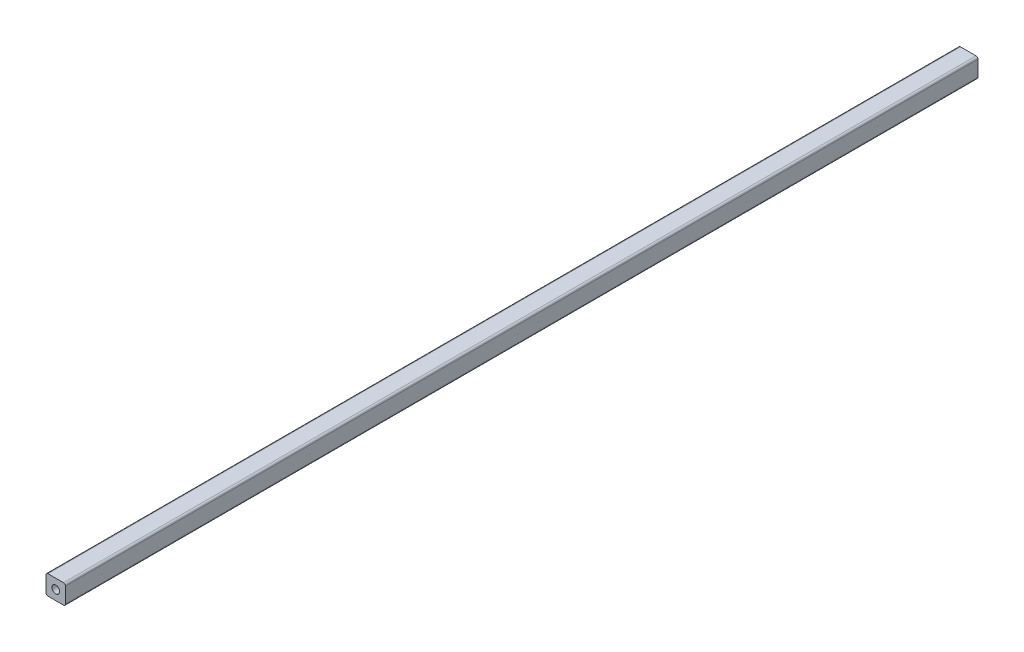
SolidWorks part; units mm, degrees
ref_plane "Front Plane" through (0, 0, 0) normal (0, 0, 1) x (1, 0, 0)
ref_plane "Top Plane" through (0, 0, 0) normal (0, 1, 0) x (1, 0, 0)
ref_plane "Right Plane" through (0, 0, 0) normal (1, 0, 0) x (0, 0, -1)
sketch "Sketch1" plane through (0, 0, 0) normal (0, 0, 1) x (1, 0, 0)
  line L1 (-25.4, 25.4) -> (25.4, 25.4)
  line L2 (-25.4, 25.4) -> (-25.4, -25.4)
  line L3 (-25.4, -25.4) -> (25.4, -25.4)
  line L4 (25.4, 25.4) -> (25.4, -25.4)
  line L5 (-25.4, 25.4) -> (25.4, -25.4) construction
  line L6 (-25.4, -25.4) -> (25.4, 25.4) construction
  circle A0 centre (0, 0) radius 10
  point P0 (0, 0)
  point P5 (0, 0)
  dimension "D3" = 20
  dimension "D1" = 50.8
  dimension "D2" = 50.8
extrude "Boss-Extrude1" add sketch "Sketch1" along normal blind 2381.25
fillet "Fillet1" radius 5 4 edges at (25.4, -25.4, 1190.625) (-25.4, -25.4, 1190.625) (-25.4, 25.4, 1190.625) (25.4, 25.4, 1190.625)
